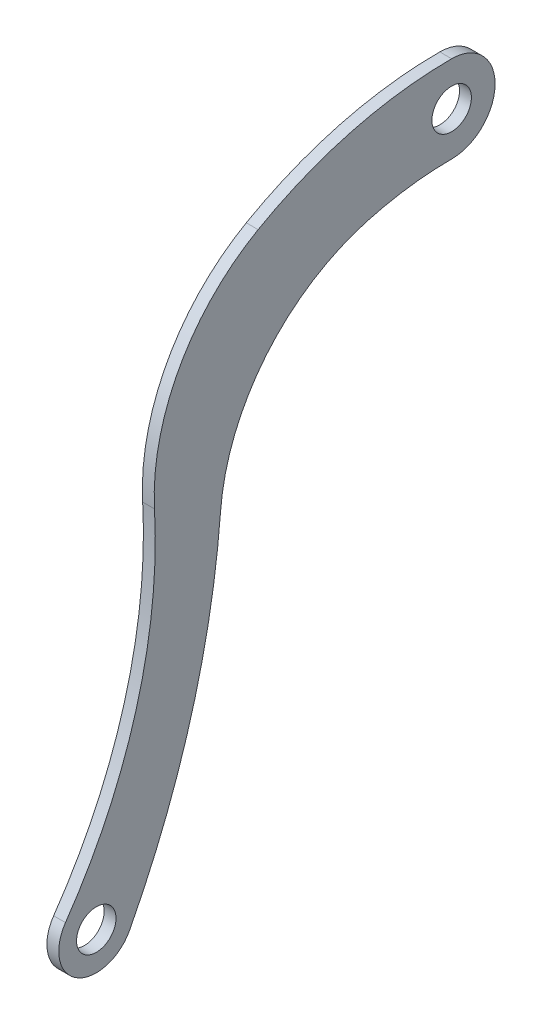
SolidWorks part; units mm, degrees
ref_plane "Front Plane" through (0, 0, 0) normal (0, 0, 1) x (1, 0, 0)
ref_plane "Top Plane" through (0, 0, 0) normal (0, 1, 0) x (1, 0, 0)
ref_plane "Right Plane" through (0, 0, 0) normal (1, 0, 0) x (0, 0, -1)
sketch "Sketch1" plane through (0, 0, 0) normal (1, 0, 0) x (0, 0, -1)
  arc A1 (0, 79) -> (0, 101) centre (0, 90) ccw
  circle A2 centre (0, 0) radius 62.05 construction
  arc A3 (0, 79) -> (-21.0371, 76.1845) centre (0, -1) ccw
  arc A4 (-58.5305, 30.9172) -> (-81.574, -49.3878) centre (-267.4567, 47.41) cw
  arc A5 (0, 101) -> (-49.0141, 88.0273) centre (0, 1.9198) ccw
  arc A6 (-49.0141, 88.0273) -> (-75.2522, 39.8944) centre (-23.2498, 42.7648) ccw
  arc A8 (-21.0371, 76.1845) -> (-58.5305, 30.9172) centre (-7.6035, 26.897) ccw
  arc A9 (-75.2522, 39.8944) -> (-97.7974, -39.5732) centre (-201.9324, 32.9021) cw
  arc A10 (-97.7974, -39.5732) -> (-81.574, -49.3878) centre (-90, -45) ccw
  point P1 (-74.9908, 32.0213)
  point P14 (-58.653, 79)
  point P15 (-75.0288, 49.6944)
  point P16 (-39.7427, 66.6239)
  point P17 (-75.2222, 33.729)
  point P18 (-77.6236, 38.2345)
  point P22 (-47.2707, 90)
  point P23 (-29.5788, 72.4436)
  point P27 (-76.1012, 49.1112)
  point P28 (-38.9711, 95.1462)
  point P29 (-74.5408, 51.9882)
  point P30 (-62.21, 93.012)
  point P31 (-49.3619, 58.2117)
  point P32 (-72.6438, 69.773)
  point P33 (-88.2945, 39.183)
  point P34 (0, 0)
  point P35 (-52.4771, 55.3266)
  point P36 (-60.046, 34.0683)
  point P37 (-91.6143, 54.3595)
  point P38 (-44.188, 85.1866)
  point P39 (-83.0776, 2.1484)
  point P40 (-49.4049, 90)
  point P41 (-77.8607, 36.5746)
  point P42 (-79.9949, 36.1003)
  point P43 (-51.0648, 87.7951)
  point P44 (-77.8607, 31.3783)
  point P45 (-76.2276, 49.1304)
  point P46 (-75.2522, 49.3797)
  point P47 (-49.1677, 90)
  point P48 (-74.5408, 47.4675)
  point P49 (-76.675, 51.2768)
  point P50 (-27.3516, 98.466)
  point P51 (-74.0666, 47.41)
  point P52 (-45.3736, 90)
  point P53 (-75.2522, 39.8944)
  dimension "D1" = 124.1
  dimension "D2" = 90
  dimension "D3" = 80
  dimension "D4" = 22
  dimension "D5" = 9.5
  dimension "D7" = 90
  dimension "D6" = 45
extrude "Boss-Extrude1" add sketch "Sketch1" along normal mid plane 3
sketch "Sketch2" plane through (1.5, 0, 0) normal (1, 0, 0) x (0, 0, -1)
  circle A0 centre (0, 90) radius 5
  circle A1 centre (-90, -45) radius 5
  dimension "D1" = 10
extrude "Cut-Extrude1" cut sketch "Sketch2" against normal through all
